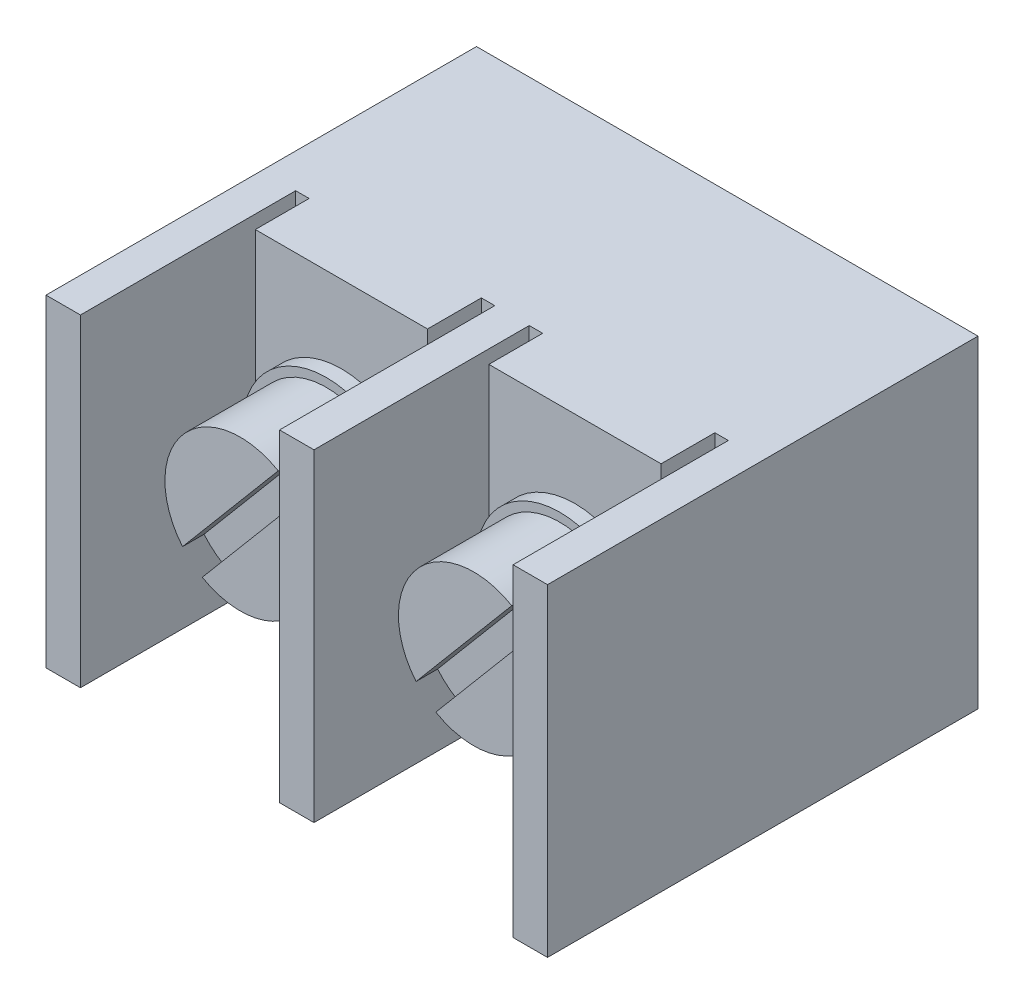
SolidWorks part; units mm, degrees
ref_plane "Спереди" through (0, 0, 0) normal (0, 0, 1) x (1, 0, 0)
ref_plane "Сверху" through (0, 0, 0) normal (0, 1, 0) x (1, 0, 0)
ref_plane "Справа" through (0, 0, 0) normal (1, 0, 0) x (0, 0, -1)
sketch "Эскиз1" plane through (0, 0, 0) normal (0, 0, 1) x (1, 0, 0)
  line L0 (-47.9787, 0) -> (44.4324, 0) construction
  line L1 (0, 0) -> (0, 38.9044) construction
  line L2 (-22.5, -7.5) -> (22.5, -7.5)
  line L3 (-22.5, -7.5) -> (-22.5, 7.5)
  line L4 (-22.5, 7.5) -> (22.5, 7.5)
  line L5 (22.5, -7.5) -> (22.5, 7.5)
  dimension "D1" = 15
  dimension "D2" = 45
extrude "Вытянуть1" add sketch "Эскиз1" along normal blind 10
sketch "Эскиз2" plane through (0, 0, 10) normal (0, 0, 1) x (1, 0, 0)
  line L0 (22.5, 7.5) -> (-22.5, 7.5) construction
  line L1 (-22.5, -7.5) -> (-20.9, -7.5)
  line L2 (-22.5, -7.5) -> (-22.5, 7.5)
  line L3 (-22.5, 7.5) -> (-20.9, 7.5)
  line L4 (-20.9, -7.5) -> (-20.9, 7.5)
  line L5 (0, 13.212) -> (0, -10.8914) construction
  line L6 (-22.5, -7.5) -> (22.5, -7.5) construction
  line L7 (-11.65, -7.5) -> (-10.05, -7.5)
  line L8 (-11.65, -7.5) -> (-11.65, 7.5)
  line L9 (-11.65, 7.5) -> (-10.05, 7.5)
  line L10 (-10.05, -7.5) -> (-10.05, 7.5)
  line L11 (-10.85, 8.3866) -> (-10.85, -8.2377) construction
  line L12 (-0.8, -7.5) -> (0.8, -7.5)
  line L13 (-0.8, -7.5) -> (-0.8, 7.5)
  line L14 (-0.8, 7.5) -> (0.8, 7.5)
  line L15 (0.8, -7.5) -> (0.8, 7.5)
  line L16 (10.05, -7.5) -> (10.05, 7.5)
  line L17 (11.65, 7.5) -> (10.05, 7.5)
  line L18 (11.65, -7.5) -> (11.65, 7.5)
  line L19 (11.65, -7.5) -> (10.05, -7.5)
  line L20 (20.9, -7.5) -> (20.9, 7.5)
  line L21 (22.5, 7.5) -> (20.9, 7.5)
  line L22 (22.5, -7.5) -> (22.5, 7.5)
  line L23 (22.5, -7.5) -> (20.9, -7.5)
  dimension "D1" = 1.6
  dimension "D2" = 10.85
extrude "Вытянуть2" add sketch "Эскиз2" along normal blind 10
sketch "Эскиз3" plane through (0, 0, 10) normal (0, 0, 1) x (1, 0, 0)
  line L0 (-16.275, 10.8914) -> (-16.275, -9.6255) construction
  line L1 (-24.3143, 0) -> (23.7342, 0) construction
  line L3 (-11.65, 7.5) -> (-11.65, -7.5) construction
  line L4 (-20.9, -7.5) -> (-20.9, 7.5) construction
  line L5 (-20.9, -7.5) -> (-11.65, -7.5) construction
  line L6 (-20.275, -7.5) -> (-12.275, -7.5)
  line L7 (-20.275, -7.5) -> (-20.275, 7.5)
  line L8 (-20.275, 7.5) -> (-12.275, 7.5)
  line L9 (-12.275, -7.5) -> (-12.275, 7.5)
  line L10 (-11.65, 7.5) -> (-20.9, 7.5) construction
  line L11 (-9.425, -7.5) -> (-1.425, -7.5)
  line L12 (-9.425, -7.5) -> (-9.425, 7.5)
  line L13 (-9.425, 7.5) -> (-1.425, 7.5)
  line L14 (-1.425, -7.5) -> (-1.425, 7.5)
  line L15 (1.425, -7.5) -> (9.425, -7.5)
  line L16 (1.425, -7.5) -> (1.425, 7.5)
  line L17 (1.425, 7.5) -> (9.425, 7.5)
  line L18 (9.425, -7.5) -> (9.425, 7.5)
  line L19 (12.275, -7.5) -> (20.275, -7.5)
  line L20 (12.275, -7.5) -> (12.275, 7.5)
  line L21 (12.275, 7.5) -> (20.275, 7.5)
  line L22 (20.275, -7.5) -> (20.275, 7.5)
  dimension "D1" = 8
extrude "Вытянуть3" add sketch "Эскиз3" along normal blind 2.5
sketch "Эскиз4" plane through (0, 0, 12.5) normal (0, 0, 1) x (1, 0, 0)
  line L0 (-24.2616, 0) -> (23.4177, 0) construction
  line L1 (-16.275, 10.7331) -> (-16.275, -8.9399) construction
  line L2 (-20.275, 7.5) -> (-20.275, -7.5) construction
  line L3 (-12.275, -7.5) -> (-12.275, 7.5) construction
  circle A0 centre (-16.275, 0) radius 3.9
  circle A1 centre (-5.425, 0) radius 3.9
  circle A2 centre (5.425, 0) radius 3.9
  circle A3 centre (16.275, 0) radius 3.9
  circle A42 centre (70.525, 0) radius 3.9 [skipped]
  circle A43 centre (81.375, 0) radius 3.9 [skipped]
  circle A44 centre (92.225, 0) radius 3.9 [skipped]
  circle A45 centre (103.075, 0) radius 3.9 [skipped]
  circle A46 centre (113.925, 0) radius 3.9 [skipped]
  circle A47 centre (124.775, 0) radius 3.9 [skipped]
  circle A48 centre (135.625, 0) radius 3.9 [skipped]
  circle A49 centre (146.475, 0) radius 3.9 [skipped]
  circle A50 centre (157.325, 0) radius 3.9 [skipped]
  circle A51 centre (168.175, 0) radius 3.9 [skipped]
  circle A52 centre (179.025, 0) radius 3.9 [skipped]
  circle A53 centre (189.875, 0) radius 3.9 [skipped]
  circle A54 centre (200.725, 0) radius 3.9 [skipped]
  circle A55 centre (211.575, 0) radius 3.9 [skipped]
  circle A56 centre (222.425, 0) radius 3.9 [skipped]
  circle A57 centre (233.275, 0) radius 3.9 [skipped]
  circle A58 centre (244.125, 0) radius 3.9 [skipped]
  circle A59 centre (254.975, 0) radius 3.9 [skipped]
  circle A60 centre (265.825, 0) radius 3.9 [skipped]
  circle A61 centre (276.675, 0) radius 3.9 [skipped]
  circle A62 centre (287.525, 0) radius 3.9 [skipped]
  circle A63 centre (298.375, 0) radius 3.9 [skipped]
  circle A64 centre (309.225, 0) radius 3.9 [skipped]
  circle A65 centre (320.075, 0) radius 3.9 [skipped]
  circle A66 centre (330.925, 0) radius 3.9 [skipped]
  circle A67 centre (341.775, 0) radius 3.9 [skipped]
  circle A68 centre (352.625, 0) radius 3.9 [skipped]
  circle A69 centre (363.475, 0) radius 3.9 [skipped]
  circle A70 centre (374.325, 0) radius 3.9 [skipped]
  circle A71 centre (385.175, 0) radius 3.9 [skipped]
  circle A72 centre (396.025, 0) radius 3.9 [skipped]
  circle A73 centre (406.875, 0) radius 3.9 [skipped]
  circle A74 centre (417.725, 0) radius 3.9 [skipped]
  circle A75 centre (428.575, 0) radius 3.9 [skipped]
  circle A76 centre (27.125, 0) radius 3.9 [skipped]
  circle A77 centre (37.975, 0) radius 3.9 [skipped]
  circle A78 centre (48.825, 0) radius 3.9 [skipped]
  circle A79 centre (59.675, 0) radius 3.9 [skipped]
  dimension "D1" = 7.8
extrude "Вытянуть4" add sketch "Эскиз4" along normal blind 0.7
sketch "Эскиз6" plane through (0, 0, 13.2) normal (0, 0, 1) x (1, 0, 0)
  circle A0 centre (-16.275, 0) radius 3.5
  circle A1 centre (-16.275, 0) radius 3.9 construction
  circle A2 centre (-5.425, 0) radius 3.5
  circle A3 centre (5.425, 0) radius 3.5
  circle A4 centre (16.275, 0) radius 3.5
  dimension "D1" = 7
extrude "Вытянуть5" add sketch "Эскиз6" along normal blind 4
sketch "Эскиз7" plane through (0, 0, 17.2) normal (0, 0, 1) x (1, 0, 0)
  line L0 (-16.275, 0) -> (-11.0149, 0.4476) construction
  line L1 (-16.275, 0) -> (-12.9483, 3.9455) construction
  line L2 (-14.511, 3.0229) -> (-18.9564, -2.2494)
  line L3 (-13.5936, 2.2494) -> (-18.039, -3.0229)
  line L4 (-3.661, 3.0229) -> (-8.1064, -2.2494)
  line L5 (-2.7436, 2.2494) -> (-7.189, -3.0229)
  line L6 (7.189, 3.0229) -> (2.7436, -2.2494)
  line L7 (8.1064, 2.2494) -> (3.661, -3.0229)
  line L8 (18.039, 3.0229) -> (13.5936, -2.2494)
  line L9 (18.9564, 2.2494) -> (14.511, -3.0229)
  circle A0 centre (-16.275, 0) radius 3.5 construction
  arc A1 (-13.5936, 2.2494) -> (-14.511, 3.0229) centre (-16.275, 0) ccw
  arc A2 (-18.9564, -2.2494) -> (-18.039, -3.0229) centre (-16.275, 0) ccw
  arc A3 (-2.7436, 2.2494) -> (-3.661, 3.0229) centre (-5.425, 0) ccw
  arc A4 (-8.1064, -2.2494) -> (-7.189, -3.0229) centre (-5.425, 0) ccw
  arc A5 (8.1064, 2.2494) -> (7.189, 3.0229) centre (5.425, 0) ccw
  arc A6 (2.7436, -2.2494) -> (3.661, -3.0229) centre (5.425, 0) ccw
  arc A7 (18.9564, 2.2494) -> (18.039, 3.0229) centre (16.275, 0) ccw
  arc A8 (13.5936, -2.2494) -> (14.511, -3.0229) centre (16.275, 0) ccw
  dimension "D1" = 45
  dimension "D2" = 1.2
extrude "Вырез-Вытянуть1" cut sketch "Эскиз7" against normal blind 1
sketch "Эскиз8" plane through (0, 0, 0) normal (0, 0, -1) x (-1, 0, 0)
  line L0 (-23.7342, 0) -> (23.7342, 0) construction
  line L1 (0, 12.8956) -> (0, -12.4209) construction
  circle A0 centre (-5, 0) radius 0.85
  circle A1 centre (5, 0) radius 0.85
  circle A2 centre (15, 0) radius 0.85
  circle A3 centre (-15, 0) radius 0.85
  dimension "D1" = 10
  dimension "D2" = 30
  dimension "D3" = 1.7
extrude "Вытянуть6" add sketch "Эскиз8" along normal blind 2.5
sketch "Эскиз10" plane through (22.5, 0, 0) normal (1, 0, 0) x (0, 0, -1)
  line L1 (-21.8513, -9.5728) -> (4.5728, -9.5728)
  line L2 (-21.8513, -9.5728) -> (-21.8513, 10.269)
  line L3 (-21.8513, 10.269) -> (4.5728, 10.269)
  line L4 (4.5728, -9.5728) -> (4.5728, 10.269)
extrude "Вырез-Вытянуть2" cut sketch "Эскиз10" against normal up to surface (21.7 mm away) up to face at (0.8, 0, 15)
